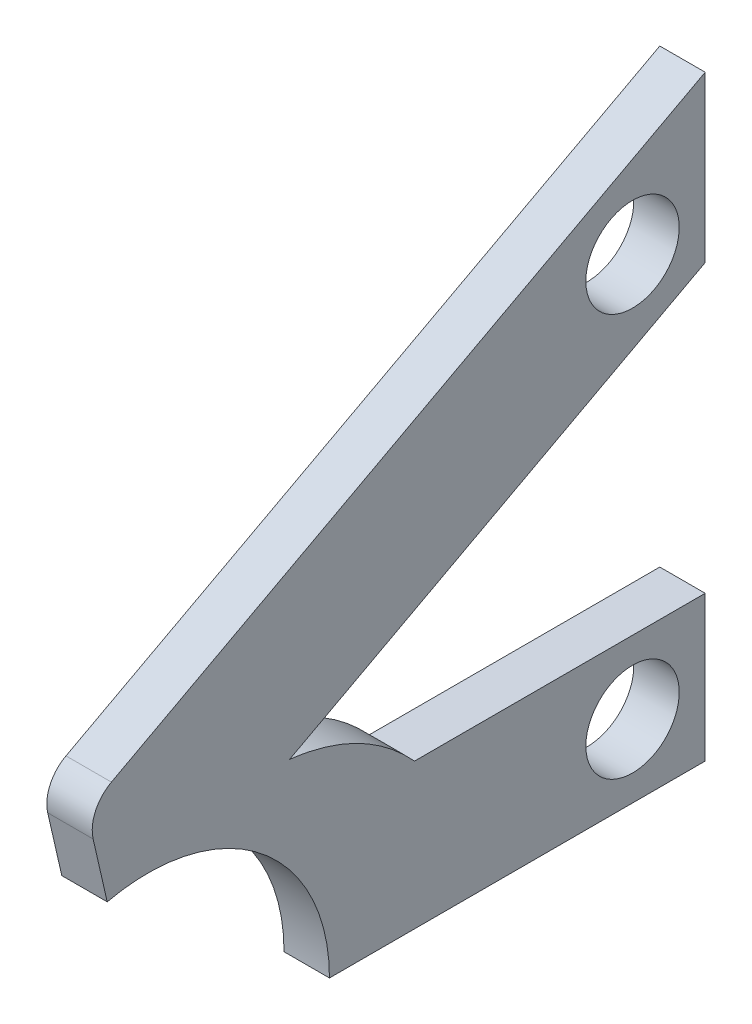
SolidWorks part; units mm, degrees
material "AISI 4130 Steel, annealed at 865C"
ref_plane "Front Plane" through (0, 0, 0) normal (0, 0, 1) x (1, 0, 0)
ref_plane "Top Plane" through (0, 0, 0) normal (0, 1, 0) x (1, 0, 0)
ref_plane "Right Plane" through (0, 0, 0) normal (1, 0, 0) x (0, 0, -1)
sketch "Sketch2" plane through (-112.555, 0, -573.5897) normal (-1, 0, 0) x (0, 0.6231, 0.7821)
  line L0 (843.7852, 138.5824) -> (864.3306, 122.2137)
  line L1 (871.0899, 172.8543) -> (811.2713, 97.7721) construction
  line L2 (864.3306, 122.2137) -> (884.1965, 122.2137) construction
  line L3 (884.1965, 122.2137) -> (887.6455, 124.9615)
  line L4 (850.1161, 146.5287) -> (866.0089, 133.8669)
  line L5 (888.3957, 127.9526) -> (869.774, 171.2026)
  line L6 (875.6249, 131.922) -> (862.593, 162.1893)
  line L7 (843.7852, 138.5824) -> (850.1161, 146.5287)
  line L8 (862.593, 162.1893) -> (869.774, 171.2026)
  circle A0 centre (874.2635, 114.3) radius 12.7 construction
  arc A1 (864.3306, 122.2137) -> (884.1965, 122.2137) centre (874.2635, 114.3) cw
  arc A2 (887.6455, 124.9615) -> (888.3957, 127.9526) centre (886.0628, 126.9481) ccw
  spline S0 degree 2 poles (866.0089, 133.8669) (871.1832, 134.6851) (875.6249, 131.922) knots 0 0 0 1 1 1
  point P17 (889.163, 126.1705)
  dimension "D5" = 2.54
  dimension "D1" = 10.16
  dimension "D2" = 10.16
  dimension "D3" = 6.35
  dimension "D4" = 20.32
extrude "Boss-Extrude1" add sketch "Sketch2" along normal blind 3.175 contours L4 S0 L6 L8 L5 A2 L3 A1 L0 L7
sketch "Sketch7" plane through (-115.73, 0, 0) normal (-1, 0, 0) x (0, 0, 1)
  line L0 (0, 644.3314) -> (20.32, 644.3314) construction
  line L1 (0, 634.1714) -> (0, 644.3314) construction
  line L2 (41.5146, 653.6555) -> (0, 675.8787) construction
  circle A0 centre (5.08, 639.2514) radius 3.2639
  circle A1 centre (5.08, 667.3973) radius 3.2639
  point P10 (0, 0)
  point P12 (0, 0)
  point P13 (0, 0)
  dimension "D1" = 5.08
  dimension "D2" = 5.08
  dimension "D3" = 5.08
  dimension "D5" = 6.5278
extrude "Cut-Extrude3" cut sketch "Sketch7" against normal through all
